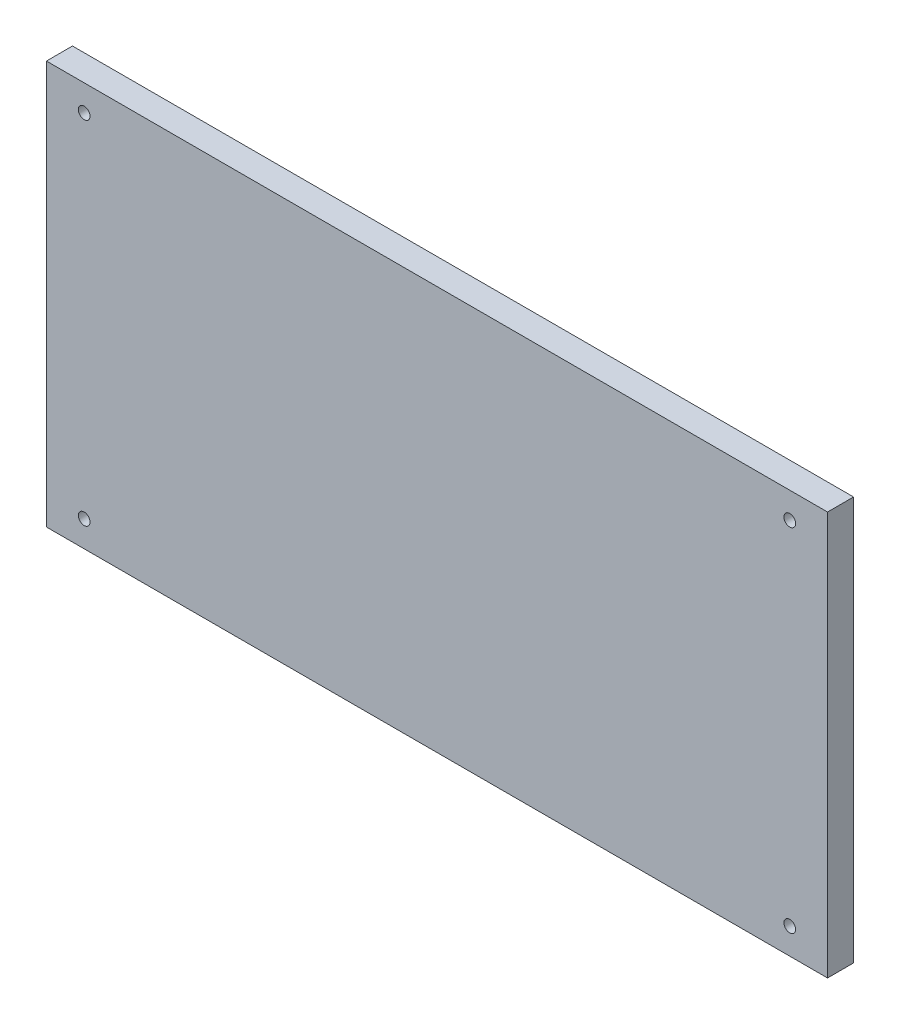
SolidWorks part; units mm, degrees
ref_plane "Plan de face" through (0, 0, 0) normal (0, 0, 1) x (1, 0, 0)
ref_plane "Plan de dessus" through (0, 0, 0) normal (0, 1, 0) x (1, 0, 0)
ref_plane "Plan de droite" through (0, 0, 0) normal (1, 0, 0) x (0, 0, -1)
sketch "Esquisse1" plane through (0, 0, 0) normal (0, 0, 1) x (1, 0, 0)
  line L1 (-122.4446, 41.9355) -> (177.5554, 41.9355)
  line L2 (-122.4446, 41.9355) -> (-122.4446, -113.0645)
  line L3 (-122.4446, -113.0645) -> (177.5554, -113.0645)
  line L4 (177.5554, 41.9355) -> (177.5554, -113.0645)
  dimension "D1" = 300
  dimension "D2" = 155
extrude "Boss.-Extru.1" add sketch "Esquisse1" along normal blind 10
sketch "Esquisse2" plane through (0, 0, 0) normal (0, 0, -1) x (-1, 0, 0)
  line L0 (-177.5554, -113.0645) -> (-177.5554, 41.9355) construction
  line L1 (122.4446, -113.0645) -> (-177.5554, -113.0645) construction
  line L2 (-177.5554, 41.9355) -> (122.4446, 41.9355) construction
  line L3 (122.4446, 41.9355) -> (122.4446, -113.0645) construction
  circle A0 centre (-163.0554, -103.0645) radius 2.25
  circle A1 centre (-163.0554, 31.9355) radius 2.25
  circle A2 centre (107.9446, 31.9355) radius 2.25
  circle A3 centre (107.9446, -103.0645) radius 2.25
  dimension "D1" = 4.5
  dimension "D2" = 4.5
  dimension "D3" = 4.5
  dimension "D4" = 4.5
  dimension "D6" = 10
  dimension "D11" = 14.5
  dimension "D5" = 14.5
  dimension "D7" = 10
  dimension "D8" = 14.5
  dimension "D9" = 10
  dimension "D10" = 14.5
  dimension "D12" = 10
extrude "Enlèv. mat.-Extru.1" cut sketch "Esquisse2" against normal blind 10
